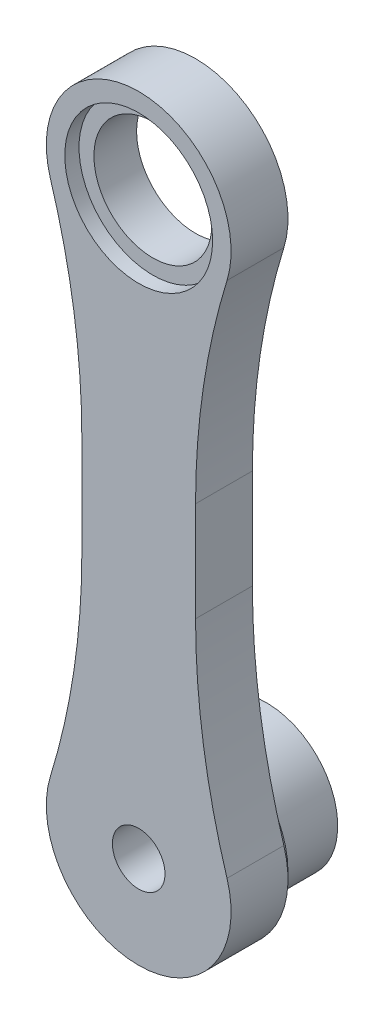
SolidWorks part; units mm, degrees
ref_plane "Front Plane" through (0, 0, 0) normal (0, 0, 1) x (1, 0, 0)
ref_plane "Top Plane" through (0, 0, 0) normal (0, 1, 0) x (1, 0, 0)
ref_plane "Right Plane" through (0, 0, 0) normal (1, 0, 0) x (0, 0, -1)
sketch "草图1" plane through (0, 0, 0) normal (0, 0, 1) x (1, 0, 0)
  line L0 (-13.8125, -26.452) -> (19.4711, -26.452) construction
  line L2 (-6, -11.452) -> (-6, -41.452)
  line L4 (2, -11.452) -> (2, -41.452)
  arc A0 (2, -41.452) -> (-6, -41.452) centre (-2, -46.5755) cw
  circle A8 centre (-2, -6.3285) radius 4.15
  arc A9 (2, -11.452) -> (-6, -11.452) centre (-2, -6.3285) ccw
  point P3 (-6, -26.452)
  point P11 (-6, -26.452)
  point P12 (6, -11.452)
  point P13 (2, -26.452)
  dimension "D6" = 6.5
  dimension "D2" = 8.3
  dimension "D1" = 15
  dimension "D3" = 8
extrude "凸台-拉伸1" add sketch "草图1" along normal blind 4
fillet "圆角1" radius 50 4 edges at (-6, -41.452, 2) (2, -41.452, 2) (-6, -11.452, 2) (2, -11.452, 2)
sketch "草图4" plane through (0, 0, 0) normal (0, 0, -1) x (-1, 0, 0)
  circle A0 centre (2, -46.5755) radius 5
  dimension "D1" = 10
extrude "凸台-拉伸2" add sketch "草图4" along normal blind 5
sketch "草图5" plane through (0, 0, 0) normal (0, 0, -1) x (-1, 0, 0)
  circle A0 centre (2, -46.5755) radius 6
extrude "凸台-拉伸3" add sketch "草图5" along normal blind 0.5
sketch "草图6" plane through (0, 0, -5) normal (0, 0, -1) x (-1, 0, 0)
  circle A0 centre (2, -46.5755) radius 3.15
  dimension "D1" = 6.3
extrude "切除-拉伸2" cut sketch "草图6" against normal blind 3
sketch "草图7" plane through (0, 0, -2) normal (0, 0, -1) x (-1, 0, 0)
  circle A0 centre (2, -46.5755) radius 1.85
  dimension "D1" = 3.7
extrude "切除-拉伸3" cut sketch "草图7" against normal blind 10
sketch "草图8" plane through (0, 0, 4) normal (0, 0, 1) x (1, 0, 0)
  circle A0 centre (-2, -6.3285) radius 5.2
  dimension "D1" = 10.4
extrude "切除-拉伸4" cut sketch "草图8" against normal blind 1
